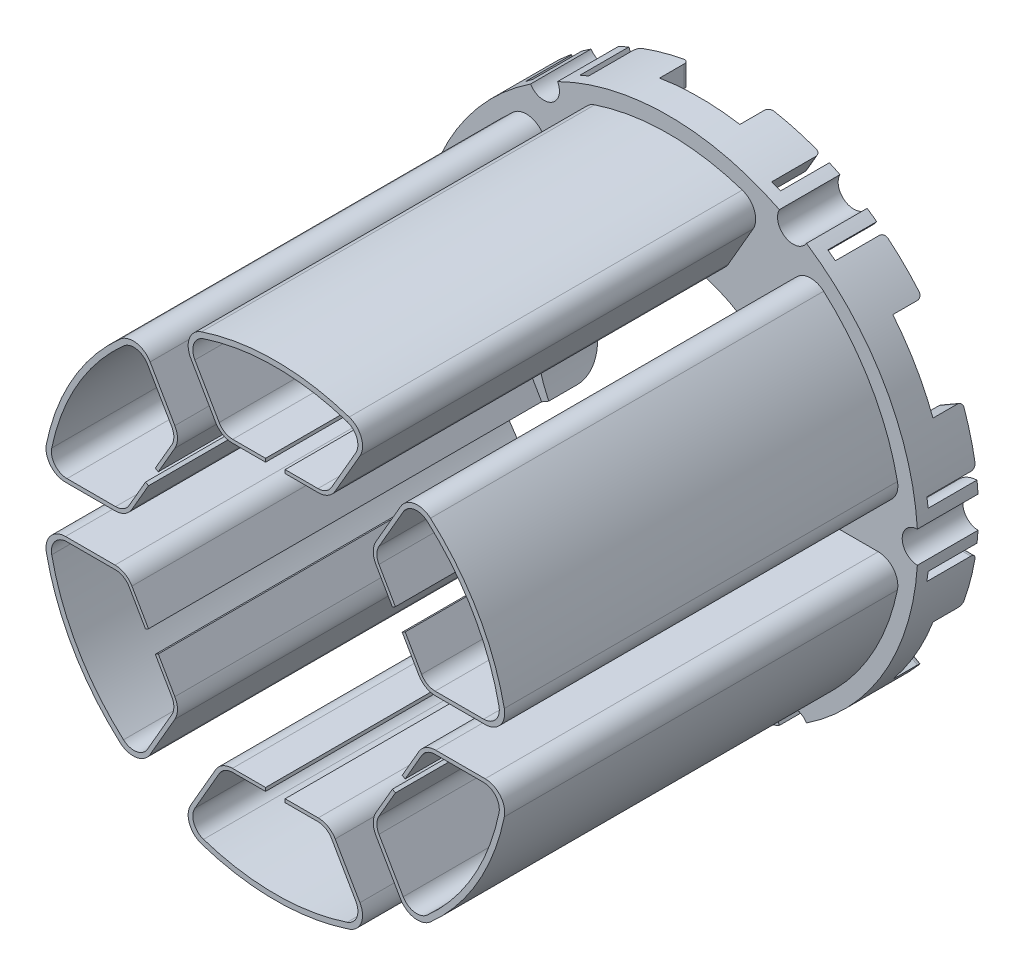
SolidWorks part; units mm, degrees
ref_plane "Ön Düzlem" through (0, 0, 0) normal (0, 0, 1) x (1, 0, 0)
ref_plane "Üst Düzlem" through (0, 0, 0) normal (0, 1, 0) x (1, 0, 0)
ref_plane "Sağ Düzlem" through (0, 0, 0) normal (1, 0, 0) x (0, 0, -1)
sketch "Çizim1" plane through (0, 0, 0) normal (0, 0, 1) x (1, 0, 0)
  line L0 (-5.5426, 14.4) -> (5.5426, 14.4)
  line L1 (9.6995, 12) -> (15.242, 2.4)
  line L2 (15.242, -2.4) -> (9.6995, -12)
  line L3 (5.5426, -14.4) -> (-5.5426, -14.4)
  line L4 (-9.6995, -12) -> (-15.242, -2.4)
  line L5 (-15.242, 2.4) -> (-9.6995, 12)
  line L7 (15.242, 2.4) -> (23.7792, 2.4)
  line L9 (9.6995, 12) -> (13.9681, 19.3934)
  line L10 (9.6995, -12) -> (13.9681, -19.3934)
  line L12 (-5.5426, 14.4) -> (-9.8111, 21.7934)
  line L13 (5.5426, 14.4) -> (9.8111, 21.7934)
  line L14 (15.242, -2.4) -> (23.7792, -2.4)
  line L15 (-5.5426, -14.4) -> (-9.8111, -21.7934)
  line L17 (5.5426, -14.4) -> (9.8111, -21.7934)
  line L18 (-15.242, -2.4) -> (-23.7792, -2.4)
  line L20 (-9.6995, -12) -> (-13.9681, -19.3934)
  line L21 (-9.6995, 12) -> (-13.9681, 19.3934)
  line L23 (-15.242, 2.4) -> (-23.7792, 2.4)
  arc A0 (-23.7792, -2.4) -> (-13.9681, -19.3934) centre (0, 0) ccw
  arc A1 (-13.9681, 19.3934) -> (-23.7792, 2.4) centre (0, 0) ccw
  arc A2 (9.8111, 21.7934) -> (-9.8111, 21.7934) centre (0, 0) ccw
  arc A3 (23.7792, 2.4) -> (13.9681, 19.3934) centre (0, 0) ccw
  arc A4 (13.9681, -19.3934) -> (23.7792, -2.4) centre (0, 0) ccw
  arc A5 (-9.8111, -21.7934) -> (9.8111, -21.7934) centre (0, 0) ccw
  point P6 (0, 14.4)
  point P18 (0, 0)
  point P32 (0, 0)
  point P43 (0, 0)
  dimension "D1" = 47.8
  dimension "D2" = 6
  dimension "D3" = 4.8
  dimension "D4" = 28.8
  dimension "D5" = 120
  dimension "D7" = 120
  dimension "D6" = 6
extrude "Yükseklik-Ekstrüzyon1" add sketch "Çizim1" along normal blind 40.2
sketch "Çizim2" plane through (0, 0, 0) normal (0, 0, -1) x (-1, 0, 0)
  circle A0 centre (0, 0) radius 25.5
  circle A1 centre (0, 0) radius 13.6
  dimension "D1" = 51
  dimension "D2" = 27.2
extrude "Yükseklik-Ekstrüzyon2" add sketch "Çizim2" along normal blind 1.2
sketch "Çizim3" plane through (0, 0, 40.2) normal (0, 0, 1) x (1, 0, 0)
  line L36 (-10.5944, 12.75) -> (-13.075, 17.0466)
  line L37 (-21.3003, 2.8) -> (-16.339, 2.8)
  line L38 (-14.9534, 3.6) -> (-10.5944, 11.15)
  line L39 (4.359, -14.75) -> (-4.359, -14.75)
  line L40 (-5.7446, -15.55) -> (-8.2253, -19.8466)
  line L41 (8.2253, -19.8466) -> (5.7446, -15.55)
  line L42 (-16.339, -2.8) -> (-21.3003, -2.8)
  line L43 (-13.075, -17.0466) -> (-10.5944, -12.75)
  line L44 (-10.5944, -11.15) -> (-14.9534, -3.6)
  line L45 (21.3003, -2.8) -> (16.339, -2.8)
  line L46 (14.9534, -3.6) -> (10.5944, -11.15)
  line L47 (10.5944, -12.75) -> (13.075, -17.0466)
  line L48 (13.075, 17.0466) -> (10.5944, 12.75)
  line L49 (10.5944, 11.15) -> (14.9534, 3.6)
  line L50 (16.339, 2.8) -> (21.3003, 2.8)
  line L51 (5.7446, 15.55) -> (8.2253, 19.8466)
  line L52 (-8.2253, 19.8466) -> (-5.7446, 15.55)
  line L53 (-4.359, 14.75) -> (4.359, 14.75)
  arc A60 (-13.075, 17.0466) -> (-15.5244, 17.4417) centre (-14.4607, 16.2466) ccw
  arc A61 (-15.5244, 17.4417) -> (-22.8672, 4.7237) centre (0, 0) ccw
  arc A62 (-22.8672, 4.7237) -> (-21.3003, 2.8) centre (-21.3003, 4.4) ccw
  arc A63 (-16.339, 2.8) -> (-14.9534, 3.6) centre (-16.339, 4.4) ccw
  arc A64 (-10.5944, 11.15) -> (-10.5944, 12.75) centre (-11.98, 11.95) ccw
  arc A65 (-4.359, -14.75) -> (-5.7446, -15.55) centre (-4.359, -16.35) ccw
  arc A66 (-8.2253, -19.8466) -> (-7.3428, -22.1654) centre (-6.8396, -20.6466) ccw
  arc A67 (-7.3428, -22.1654) -> (7.3428, -22.1654) centre (0, 0) ccw
  arc A68 (7.3428, -22.1654) -> (8.2253, -19.8466) centre (6.8396, -20.6466) ccw
  arc A69 (5.7446, -15.55) -> (4.359, -14.75) centre (4.359, -16.35) ccw
  arc A70 (-21.3003, -2.8) -> (-22.8672, -4.7237) centre (-21.3003, -4.4) ccw
  arc A71 (-22.8672, -4.7237) -> (-15.5244, -17.4417) centre (0, 0) ccw
  arc A72 (-15.5244, -17.4417) -> (-13.075, -17.0466) centre (-14.4607, -16.2466) ccw
  arc A73 (-10.5944, -12.75) -> (-10.5944, -11.15) centre (-11.98, -11.95) ccw
  arc A74 (-14.9534, -3.6) -> (-16.339, -2.8) centre (-16.339, -4.4) ccw
  arc A75 (16.339, -2.8) -> (14.9534, -3.6) centre (16.339, -4.4) ccw
  arc A76 (10.5944, -11.15) -> (10.5944, -12.75) centre (11.98, -11.95) ccw
  arc A77 (13.075, -17.0466) -> (15.5244, -17.4417) centre (14.4607, -16.2466) ccw
  arc A78 (15.5244, -17.4417) -> (22.8672, -4.7237) centre (0, 0) ccw
  arc A79 (22.8672, -4.7237) -> (21.3003, -2.8) centre (21.3003, -4.4) ccw
  arc A80 (22.8672, 4.7237) -> (15.5244, 17.4417) centre (0, 0) ccw
  arc A81 (15.5244, 17.4417) -> (13.075, 17.0466) centre (14.4607, 16.2466) ccw
  arc A82 (10.5944, 12.75) -> (10.5944, 11.15) centre (11.98, 11.95) ccw
  arc A83 (14.9534, 3.6) -> (16.339, 2.8) centre (16.339, 4.4) ccw
  arc A84 (21.3003, 2.8) -> (22.8672, 4.7237) centre (21.3003, 4.4) ccw
  arc A85 (8.2253, 19.8466) -> (7.3428, 22.1654) centre (6.8396, 20.6466) ccw
  arc A86 (7.3428, 22.1654) -> (-7.3428, 22.1654) centre (0, 0) ccw
  arc A87 (-7.3428, 22.1654) -> (-8.2253, 19.8466) centre (-6.8396, 20.6466) ccw
  arc A88 (-5.7446, 15.55) -> (-4.359, 14.75) centre (-4.359, 16.35) ccw
  arc A89 (4.359, 14.75) -> (5.7446, 15.55) centre (4.359, 16.35) ccw
extrude "Kes-Ekstrüzyon1" cut sketch "Çizim3" against normal up to surface (41.4 mm away) up to face at (-25.5, 0, -1.2)
sketch "Çizim4" plane through (0, 0, 40.2) normal (0, 0, 1) x (1, 0, 0)
  line L0 (-4.359, 14.75) -> (4.359, 14.75) construction
  line L1 (-1, 12.25) -> (1, 12.25)
  line L2 (-1, 12.25) -> (-1, 14.75)
  line L3 (-1, 14.75) -> (1, 14.75)
  line L4 (1, 12.25) -> (1, 14.75)
  line L5 (-1, 12.25) -> (1, 14.75) construction
  line L6 (-1, 14.75) -> (1, 12.25) construction
  line L7 (10.1088, 6.991) -> (12.2739, 8.241)
  line L8 (10.1088, 6.991) -> (11.1088, 5.259)
  line L9 (11.1088, 5.259) -> (13.2739, 6.509)
  line L10 (12.2739, 8.241) -> (13.2739, 6.509)
  line L11 (11.1088, -5.259) -> (13.2739, -6.509)
  line L12 (11.1088, -5.259) -> (10.1088, -6.991)
  line L13 (10.1088, -6.991) -> (12.2739, -8.241)
  line L14 (13.2739, -6.509) -> (12.2739, -8.241)
  line L15 (1, -12.25) -> (1, -14.75)
  line L16 (1, -12.25) -> (-1, -12.25)
  line L17 (-1, -12.25) -> (-1, -14.75)
  line L18 (1, -14.75) -> (-1, -14.75)
  line L19 (-10.1088, -6.991) -> (-12.2739, -8.241)
  line L20 (-10.1088, -6.991) -> (-11.1088, -5.259)
  line L21 (-11.1088, -5.259) -> (-13.2739, -6.509)
  line L22 (-12.2739, -8.241) -> (-13.2739, -6.509)
  line L23 (-11.1088, 5.259) -> (-13.2739, 6.509)
  line L24 (-11.1088, 5.259) -> (-10.1088, 6.991)
  line L25 (-10.1088, 6.991) -> (-12.2739, 8.241)
  line L26 (-13.2739, 6.509) -> (-12.2739, 8.241)
  point P0 (0, 13.5)
  point P30 (0, 0)
  dimension "D1" = 2
  dimension "D2" = 2.5
  dimension "D3" = 6
extrude "Kes-Ekstrüzyon2" cut sketch "Çizim4" against normal up to surface (41.4 mm away)
fillet "Radyus1" radius 2 24 edges at (13.9681, -19.3934, 20.1) (9.6995, -12, 20.1) (9.6995, 12, 20.1) (15.242, 2.4, 20.1) (23.7792, 2.4, 20.1) (15.242, -2.4, 20.1) (23.7792, -2.4, 20.1) (-15.242, -2.4, 20.1) (-9.6995, -12, 20.1) (-5.5426, 14.4, 20.1) (5.5426, -14.4, 20.1) (-5.5426, -14.4, 20.1) (9.8111, -21.7934, 20.1) (-9.8111, -21.7934, 20.1) (-13.9681, -19.3934, 20.1) (-23.7792, -2.4, 20.1) (-9.6995, 12, 20.1) (5.5426, 14.4, 20.1) (13.9681, 19.3934, 20.1) (9.8111, 21.7934, 20.1) (-9.8111, 21.7934, 20.1) (-13.9681, 19.3934, 20.1) (-15.242, 2.4, 20.1) (-23.7792, 2.4, 20.1)
sketch "Çizim7" plane through (0, 0, -1.2) normal (0, 0, -1) x (-1, 0, 0)
  line L0 (8.2759, 21.8342) -> (9.3638, 23.7185)
  line L1 (14.771, 18.0842) -> (15.859, 19.9685)
  line L2 (23.0469, 3.75) -> (25.2228, 3.75)
  line L3 (8.2253, 19.8466) -> (5.7446, 15.55) construction
  line L4 (23.0469, -3.75) -> (25.2228, -3.75)
  line L5 (8.8198, 22.7764) -> (15.315, 19.0264) construction
  line L6 (6.985, 17.6983) -> (11.8347, 14.8983) construction
  line L7 (10.5944, 12.75) -> (13.075, 17.0466) construction
  line L8 (24.1348, 3.75) -> (24.1348, -3.75) construction
  line L9 (18.8197, 2.8) -> (18.8197, -2.8) construction
  line L10 (14.771, -18.0842) -> (15.859, -19.9685)
  line L11 (8.2759, -21.8342) -> (9.3638, -23.7185)
  line L12 (15.315, -19.0264) -> (8.8198, -22.7764) construction
  line L13 (11.8347, -14.8983) -> (6.985, -17.6983) construction
  line L14 (-8.2759, -21.8342) -> (-9.3638, -23.7185)
  line L15 (-14.771, -18.0842) -> (-15.859, -19.9685)
  line L16 (-8.8198, -22.7764) -> (-15.315, -19.0264) construction
  line L17 (-6.985, -17.6983) -> (-11.8347, -14.8983) construction
  line L18 (-23.0469, -3.75) -> (-25.2228, -3.75)
  line L19 (-23.0469, 3.75) -> (-25.2228, 3.75)
  line L20 (-24.1348, -3.75) -> (-24.1348, 3.75) construction
  line L21 (-18.8197, -2.8) -> (-18.8197, 2.8) construction
  line L22 (-14.771, 18.0842) -> (-15.859, 19.9685)
  line L23 (-8.2759, 21.8342) -> (-9.3638, 23.7185)
  line L24 (-15.315, 19.0264) -> (-8.8198, 22.7764) construction
  line L25 (-11.8347, 14.8983) -> (-6.985, 17.6983) construction
  arc A0 (8.2759, 21.8342) -> (-8.2759, 21.8342) centre (0, 0) ccw
  arc A1 (9.3638, 23.7185) -> (-9.3638, 23.7185) centre (0, 0) ccw
  arc A2 (-14.771, 18.0842) -> (-23.0469, 3.75) centre (0, 0) ccw
  circle A3 centre (0, 0) radius 25.5
  arc A4 (-15.859, 19.9685) -> (-25.2228, 3.75) centre (0, 0) ccw
  arc A5 (23.0469, 3.75) -> (14.771, 18.0842) centre (0, 0) ccw
  arc A6 (25.2228, 3.75) -> (15.859, 19.9685) centre (0, 0) ccw
  arc A7 (14.771, -18.0842) -> (23.0469, -3.75) centre (0, 0) ccw
  arc A8 (15.859, -19.9685) -> (25.2228, -3.75) centre (0, 0) ccw
  arc A9 (-9.3638, -23.7185) -> (9.3638, -23.7185) centre (0, 0) ccw
  arc A10 (-8.2759, -21.8342) -> (8.2759, -21.8342) centre (0, 0) ccw
  arc A11 (-23.0469, -3.75) -> (-14.771, -18.0842) centre (0, 0) ccw
  arc A12 (-25.2228, -3.75) -> (-15.859, -19.9685) centre (0, 0) ccw
  point P60 (0, 0)
  dimension "D2" = 46.7
  dimension "D1" = 0
  dimension "D3" = 7.5
  dimension "D4" = 6
extrude "Yükseklik-Ekstrüzyon3" add sketch "Çizim7" along normal blind 5
sketch "Çizim8" plane through (0, 0, -6.2) normal (0, 0, -1) x (-1, 0, 0)
  line L0 (4.1083, 25.1669) -> (4.0972, 22.9877)
  line L1 (-4.1028, 25.1678) -> (-4.1028, 22.9867)
  line L3 (-1, 13.5632) -> (-1, 14.75) construction
  line L4 (4.1028, 24.0773) -> (-4.1028, 24.0773) construction
  line L5 (-3.693, 0) -> (3.693, 0) construction
  line L30 (23.8493, 9.0256) -> (21.9566, 7.9455)
  line L31 (19.7446, 16.137) -> (17.8557, 15.0465)
  line L32 (19.741, -16.1413) -> (17.8593, -15.0422)
  line L33 (23.8473, -9.0308) -> (21.9585, -7.9403)
  line L34 (-4.1083, -25.1669) -> (-4.0972, -22.9877)
  line L35 (4.1028, -25.1678) -> (4.1028, -22.9867)
  line L36 (-23.8493, -9.0256) -> (-21.9566, -7.9455)
  line L37 (-19.7446, -16.137) -> (-17.8557, -15.0465)
  line L38 (-19.741, 16.1413) -> (-17.8593, 15.0422)
  line L39 (-23.8473, 9.0308) -> (-21.9585, 7.9403)
  arc A0 (9.3638, 23.7185) -> (-9.3638, 23.7185) centre (0, 0) ccw construction
  arc A1 (8.2759, 21.8342) -> (-8.2759, 21.8342) centre (0, 0) ccw construction
  arc A2 (-23.0469, -3.75) -> (-14.771, -18.0842) centre (0, 0) ccw construction
  arc A3 (-25.2228, -3.75) -> (-15.859, -19.9685) centre (0, 0) ccw construction
  arc A4 (14.771, -18.0842) -> (23.0469, -3.75) centre (0, 0) ccw construction
  arc A5 (15.859, -19.9685) -> (25.2228, -3.75) centre (0, 0) ccw construction
  arc A6 (-8.2759, -21.8342) -> (8.2759, -21.8342) centre (0, 0) ccw construction
  arc A7 (-9.3638, -23.7185) -> (9.3638, -23.7185) centre (0, 0) ccw construction
  arc A8 (23.0469, 3.75) -> (14.771, 18.0842) centre (0, 0) ccw construction
  arc A9 (25.2228, 3.75) -> (15.859, 19.9685) centre (0, 0) ccw construction
  arc A10 (-14.771, 18.0842) -> (-23.0469, 3.75) centre (0, 0) ccw construction
  arc A11 (-15.859, 19.9685) -> (-25.2228, 3.75) centre (0, 0) ccw construction
  arc A12 (-21.9566, -7.9455) -> (-17.8557, -15.0465) centre (0, 0) ccw
  arc A13 (-23.8493, -9.0256) -> (-19.7446, -16.137) centre (0, 0) ccw
  arc A14 (17.8593, -15.0422) -> (21.9585, -7.9403) centre (0, 0) ccw
  arc A15 (19.741, -16.1413) -> (23.8473, -9.0308) centre (0, 0) ccw
  arc A16 (-4.0972, -22.9877) -> (4.1028, -22.9867) centre (0, 0) ccw
  arc A17 (-4.1083, -25.1669) -> (4.1028, -25.1678) centre (0, 0) ccw
  arc A18 (21.9566, 7.9455) -> (17.8557, 15.0465) centre (0, 0) ccw
  arc A19 (23.8493, 9.0256) -> (19.7446, 16.137) centre (0, 0) ccw
  arc A20 (4.0972, 22.9877) -> (-4.1028, 22.9867) centre (0, 0) ccw
  arc A21 (4.1083, 25.1669) -> (-4.1028, 25.1678) centre (0, 0) ccw
  arc A22 (-17.8593, 15.0422) -> (-21.9585, 7.9403) centre (0, 0) ccw
  arc A23 (-19.741, 16.1413) -> (-23.8473, 9.0308) centre (0, 0) ccw
  point P20 (0, 0)
  point P22 (0, 24.0773)
  point P73 (0, 0)
  dimension "D1" = 8.2111
  dimension "D2" = 8.2
  dimension "D3" = 6
extrude "Kes-Ekstrüzyon3" cut sketch "Çizim8" against normal blind 3
sketch "Çizim9" plane through (0, 0, -1.2) normal (0, 0, -1) x (-1, 0, 0)
  line L0 (-11.2461, -7.6476) -> (-12.2739, -8.241) construction
  line L1 (-12.2739, 8.241) -> (-11.2461, 7.6476) construction
  line L2 (-1, 13.5632) -> (-1, 14.75) construction
  line L3 (1, 14.75) -> (1, 13.5632) construction
  line L4 (-12.2461, 5.9156) -> (-13.2739, 6.509) construction
  line L5 (13.2739, 6.509) -> (12.2461, 5.9156) construction
  line L6 (11.2461, 7.6476) -> (12.2739, 8.241) construction
  line L7 (12.2461, -5.9156) -> (13.2739, -6.509) construction
  line L8 (-13.2739, -6.509) -> (-12.2461, -5.9156) construction
  line L9 (12.2739, -8.241) -> (11.2461, -7.6476) construction
  line L10 (1, -13.5632) -> (1, -14.75) construction
  line L11 (-1, -14.75) -> (-1, -13.5632) construction
  line L12 (12.2011, -8.199) -> (11.2461, -7.6476)
  line L13 (1, -13.5632) -> (1, -14.6659)
  line L14 (-1, -14.6659) -> (-1, -13.5632)
  line L15 (-11.2461, -7.6476) -> (-12.2011, -8.199)
  line L16 (-13.2011, -6.4669) -> (-12.2461, -5.9156)
  line L17 (12.2461, -5.9156) -> (13.2011, -6.4669)
  line L18 (11.2461, 7.6476) -> (12.2011, 8.199)
  line L19 (13.2011, 6.4669) -> (12.2461, 5.9156)
  line L20 (-12.2461, 5.9156) -> (-13.2011, 6.4669)
  line L21 (1, 14.6659) -> (1, 13.5632)
  line L22 (-1, 13.5632) -> (-1, 14.6659)
  line L23 (-12.2011, 8.199) -> (-11.2461, 7.6476)
  arc A0 (-1, 13.5632) -> (-11.2461, 7.6476) centre (0, 0) ccw construction
  arc A1 (11.2461, 7.6476) -> (1, 13.5632) centre (0, 0) ccw construction
  arc A2 (-12.2461, 5.9156) -> (-12.2461, -5.9156) centre (0, 0) ccw construction
  arc A3 (12.2461, -5.9156) -> (12.2461, 5.9156) centre (0, 0) ccw construction
  arc A4 (1, -13.5632) -> (11.2461, -7.6476) centre (0, 0) ccw construction
  arc A5 (-11.2461, -7.6476) -> (-1, -13.5632) centre (0, 0) ccw construction
  arc A6 (1, -13.5632) -> (11.2461, -7.6476) centre (0, 0) ccw
  arc A7 (-11.2461, -7.6476) -> (-1, -13.5632) centre (0, 0) ccw
  arc A8 (12.2461, -5.9156) -> (12.2461, 5.9156) centre (0, 0) ccw
  arc A9 (-12.2461, 5.9156) -> (-12.2461, -5.9156) centre (0, 0) ccw
  arc A10 (11.2461, 7.6476) -> (1, 13.5632) centre (0, 0) ccw
  arc A11 (-1, 13.5632) -> (-11.2461, 7.6476) centre (0, 0) ccw
  arc A12 (-1, 14.6659) -> (-12.2011, 8.199) centre (0, 0) ccw
  arc A13 (-13.2011, 6.4669) -> (-13.2011, -6.4669) centre (0, 0) ccw
  arc A14 (-12.2011, -8.199) -> (-1, -14.6659) centre (0, 0) ccw
  arc A15 (1, -14.6659) -> (12.2011, -8.199) centre (0, 0) ccw
  arc A16 (13.2011, -6.4669) -> (13.2011, 6.4669) centre (0, 0) ccw
  arc A17 (12.2011, 8.199) -> (1, 14.6659) centre (0, 0) ccw
  dimension "D1" = 29.4
extrude "Yükseklik-Ekstrüzyon4" add sketch "Çizim9" along normal blind 4.7
fillet "Radyus3" radius 3 12 edges at (-12.7236, 6.1913, -5.9) (-11.7236, 7.9233, -5.9) (-12.7236, -6.1913, -5.9) (-11.7236, -7.9233, -5.9) (-1, -14.1146, -5.9) (1, -14.1146, -5.9) (11.7236, -7.9233, -5.9) (12.7236, -6.1913, -5.9) (12.7236, 6.1913, -5.9) (-1, 14.1146, -5.9) (1, 14.1146, -5.9) (11.7236, 7.9233, -5.9)
sketch "Çizim10" plane through (0, 0, -1.2) normal (0, 0, 1) x (1, 0, 0)
  line L0 (-11.541, 15.1896) -> (-7.3841, 17.5896) construction
  line L1 (-10.2768, 13) -> (-12.8052, 17.3792) construction
  line L2 (-8.6483, 19.7792) -> (-6.1199, 15.4) construction
  line L3 (-9.4625, 16.3896) -> (-16.0375, 27.7777) construction
  circle A0 centre (0, 0) radius 25.5 construction
  arc A1 (-14.1099, 21.2406) -> (-11.3399, 22.8398) centre (-12.75, 22.0836) ccw
  arc A2 (-15.0944, 20.5526) -> (-10.2519, 23.3484) centre (-12.75, 22.0836) ccw
  arc A3 (-14.1099, 21.2406) -> (-15.0944, 20.5526) centre (0, 0) ccw
  circle A4 centre (-12.75, 22.0836) radius 2.8 construction
  circle A5 centre (-12.75, 22.0836) radius 1.6 construction
  arc A6 (-10.2519, 23.3484) -> (-11.3399, 22.8398) centre (0, 0) ccw
  arc A7 (11.3399, 22.8398) -> (10.2519, 23.3484) centre (0, 0) ccw
  arc A8 (10.2519, 23.3484) -> (15.0944, 20.5526) centre (12.75, 22.0836) ccw
  arc A9 (11.3399, 22.8398) -> (14.1099, 21.2406) centre (12.75, 22.0836) ccw
  arc A10 (15.0944, 20.5526) -> (14.1099, 21.2406) centre (0, 0) ccw
  arc A11 (25.4498, 1.5992) -> (25.3463, 2.7958) centre (0, 0) ccw
  arc A12 (25.3463, 2.7958) -> (25.3463, -2.7958) centre (25.5, 0) ccw
  arc A13 (25.4498, 1.5992) -> (25.4498, -1.5992) centre (25.5, 0) ccw
  arc A14 (25.3463, -2.7958) -> (25.4498, -1.5992) centre (0, 0) ccw
  arc A15 (14.1099, -21.2406) -> (15.0944, -20.5526) centre (0, 0) ccw
  arc A16 (15.0944, -20.5526) -> (10.2519, -23.3484) centre (12.75, -22.0836) ccw
  arc A17 (14.1099, -21.2406) -> (11.3399, -22.8398) centre (12.75, -22.0836) ccw
  arc A18 (10.2519, -23.3484) -> (11.3399, -22.8398) centre (0, 0) ccw
  arc A19 (-11.3399, -22.8398) -> (-10.2519, -23.3484) centre (0, 0) ccw
  arc A20 (-10.2519, -23.3484) -> (-15.0944, -20.5526) centre (-12.75, -22.0836) ccw
  arc A21 (-11.3399, -22.8398) -> (-14.1099, -21.2406) centre (-12.75, -22.0836) ccw
  arc A22 (-15.0944, -20.5526) -> (-14.1099, -21.2406) centre (0, 0) ccw
  arc A23 (-25.4498, -1.5992) -> (-25.3463, -2.7958) centre (0, 0) ccw
  arc A24 (-25.3463, -2.7958) -> (-25.3463, 2.7958) centre (-25.5, 0) ccw
  arc A25 (-25.4498, -1.5992) -> (-25.4498, 1.5992) centre (-25.5, 0) ccw
  arc A26 (-25.3463, 2.7958) -> (-25.4498, 1.5992) centre (0, 0) ccw
  point P50 (0, 0)
  dimension "D1" = 3.2
  dimension "D2" = 1.2
  dimension "D3" = 6
extrude "Yükseklik-Ekstrüzyon5" add sketch "Çizim10" against normal up to surface (5 mm away) up to face at (-17.1009, -17.353, -6.2)
sketch "Çizim11" plane through (0, 0, -1.2) normal (0, 0, -1) x (-1, 0, 0)
  arc A0 (-14.1099, 21.2406) -> (-11.3399, 22.8398) centre (-12.75, 22.0836) ccw construction
  arc A1 (-11.3399, 22.8398) -> (-14.1099, 21.2406) centre (0, 0) ccw construction
  arc A2 (11.3399, 22.8398) -> (14.1099, 21.2406) centre (12.75, 22.0836) ccw construction
  arc A3 (14.1099, 21.2406) -> (11.3399, 22.8398) centre (0, 0) ccw construction
  arc A4 (14.1099, -21.2406) -> (11.3399, -22.8398) centre (12.75, -22.0836) ccw construction
  arc A5 (11.3399, -22.8398) -> (14.1099, -21.2406) centre (0, 0) ccw construction
  arc A6 (-11.3399, -22.8398) -> (-14.1099, -21.2406) centre (-12.75, -22.0836) ccw construction
  arc A7 (-14.1099, -21.2406) -> (-11.3399, -22.8398) centre (0, 0) ccw construction
  arc A8 (25.4498, 1.5992) -> (25.4498, -1.5992) centre (25.5, 0) ccw construction
  arc A9 (25.4498, -1.5992) -> (25.4498, 1.5992) centre (0, 0) ccw construction
  arc A10 (-25.4498, -1.5992) -> (-25.4498, 1.5992) centre (-25.5, 0) ccw construction
  arc A11 (-25.4498, 1.5992) -> (-25.4498, -1.5992) centre (0, 0) ccw construction
  arc A12 (-14.1099, 21.2406) -> (-11.3399, 22.8398) centre (-12.75, 22.0836) ccw
  arc A13 (-11.3399, 22.8398) -> (-14.1099, 21.2406) centre (0, 0) ccw
  arc A14 (11.3399, 22.8398) -> (14.1099, 21.2406) centre (12.75, 22.0836) ccw
  arc A15 (14.1099, 21.2406) -> (11.3399, 22.8398) centre (0, 0) ccw
  arc A16 (14.1099, -21.2406) -> (11.3399, -22.8398) centre (12.75, -22.0836) ccw
  arc A17 (11.3399, -22.8398) -> (14.1099, -21.2406) centre (0, 0) ccw
  arc A18 (-11.3399, -22.8398) -> (-14.1099, -21.2406) centre (-12.75, -22.0836) ccw
  arc A19 (-14.1099, -21.2406) -> (-11.3399, -22.8398) centre (0, 0) ccw
  arc A20 (25.4498, 1.5992) -> (25.4498, -1.5992) centre (25.5, 0) ccw
  arc A21 (25.4498, -1.5992) -> (25.4498, 1.5992) centre (0, 0) ccw
  arc A22 (-25.4498, -1.5992) -> (-25.4498, 1.5992) centre (-25.5, 0) ccw
  arc A23 (-25.4498, 1.5992) -> (-25.4498, -1.5992) centre (0, 0) ccw
extrude "Kes-Ekstrüzyon4" cut sketch "Çizim11" against normal up to surface (1.2 mm away) up to face at (-25.5, 0, 0)
fillet "Radyus4" radius 0.5 24 edges at (-18.8001, 15.5917, -6.2) (-15.315, 19.0264, -6.2) (-22.9029, 8.4856, -6.2) (-24.1348, 3.75, -6.2) (-24.1348, -3.75, -6.2) (-22.9029, -8.4855, -6.2) (-15.315, -19.0264, -6.2) (-18.8002, -15.5917, -6.2) (-8.8198, -22.7764, -6.2) (-4.1028, -24.0773, -6.2) (4.1028, -24.0773, -6.2) (8.8198, -22.7764, -6.2) (15.315, -19.0264, -6.2) (18.8001, -15.5917, -6.2) (-8.8198, 22.7764, -6.2) (-4.1028, 24.0773, -6.2) (4.1028, 24.0773, -6.2) (8.8198, 22.7764, -6.2) (15.315, 19.0264, -6.2) (18.8002, 15.5917, -6.2) (22.9029, 8.4855, -6.2) (24.1348, 3.75, -6.2) (24.1348, -3.75, -6.2) (22.9029, -8.4856, -6.2)
